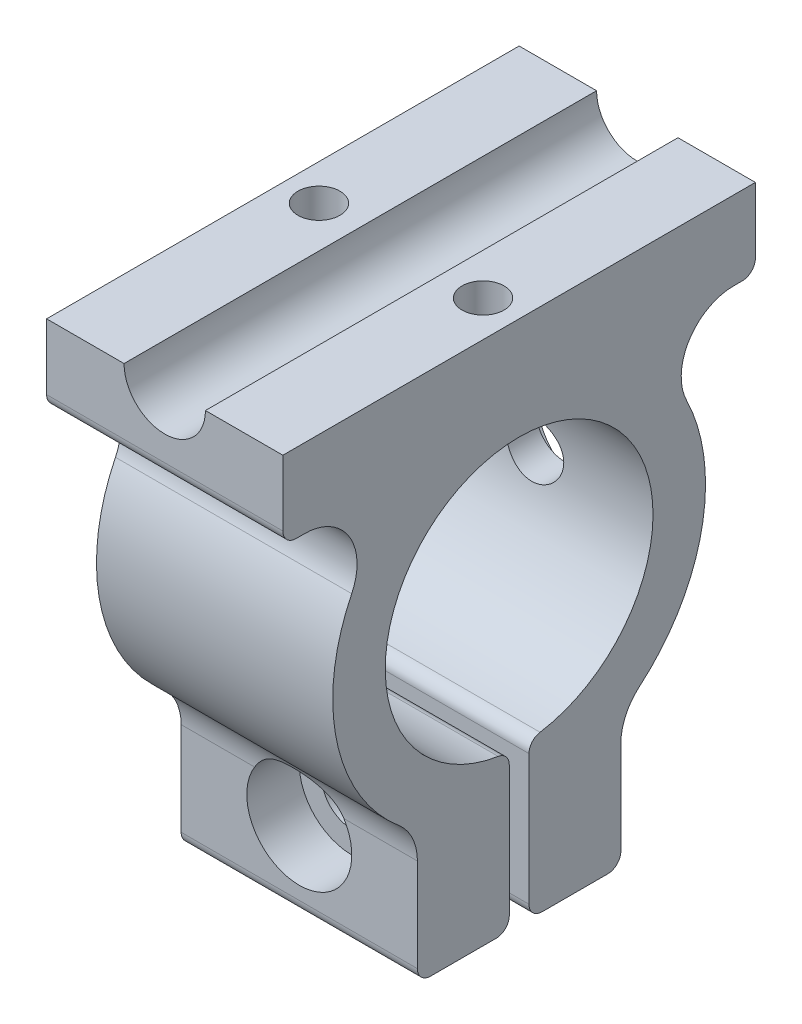
SolidWorks part; units mm, degrees
ref_plane "Спереди" through (0, 0, 0) normal (0, 0, 1) x (1, 0, 0)
ref_plane "Сверху" through (0, 0, 0) normal (0, 1, 0) x (1, 0, 0)
ref_plane "Справа" through (0, 0, 0) normal (1, 0, 0) x (0, 0, -1)
other "Configuration Table"
sketch "Эскиз1" plane through (0, 0, 0) normal (1, 0, 0) x (0, 0, -1)
  line L0 (-1001.0275, 18) -> (48998.9725, 18) construction
  line L1 (0, -1000) -> (0, 49000) construction
  line L2 (-0.75, -21) -> (-0.75, -11.0624)
  line L3 (0.75, -21) -> (0.75, -11.0624)
  line L4 (7.75, -13.8988) -> (7.75, -21)
  line L5 (-7.75, -13.8988) -> (-7.75, -21)
  line L6 (1.75, -22) -> (6.75, -22)
  line L7 (-1000, 0) -> (49000, 0) construction
  line L8 (-6.75, -22) -> (-1.75, -22)
  line L9 (-18, 18) -> (-18, 13)
  line L10 (-7.75, -6.6316) -> (-7.75, -11.8986) construction
  line L11 (7.75, -6.6316) -> (7.75, -11.8986) construction
  line L12 (-17, 12) -> (-16.3475, 12)
  line L13 (17, 12) -> (16.3475, 12)
  line L14 (18, 18) -> (18, 13)
  line L15 (-18, 18) -> (18, 18)
  arc A0 (1.5938, -10.0747) -> (-1.5938, -10.0747) centre (0, 0) ccw
  arc A1 (9.1676, -10.8441) -> (12.7546, 6.2418) centre (0, 0) ccw
  arc A2 (0, -10.2) -> (0.75, -10.1724) centre (0, 0) ccw construction
  arc A3 (-0.75, -10.1724) -> (0, -10.2) centre (0, 0) ccw construction
  arc A4 (0, -14.2) -> (0.75, -14.1802) centre (0, 0) ccw construction
  arc A5 (-0.75, -14.1802) -> (0, -14.2) centre (0, 0) ccw construction
  arc A6 (-7.75, -11.8986) -> (-0.75, -14.1802) centre (0, 0) ccw construction
  arc A7 (0.75, -14.1802) -> (7.75, -11.8986) centre (0, 0) ccw construction
  arc A8 (0, 14.2) -> (-7.5921, 12) centre (0, 0) ccw construction
  arc A9 (-12.7546, 6.2418) -> (-9.1676, -10.8441) centre (0, 0) ccw
  arc A10 (7.5921, 12) -> (0, 14.2) centre (0, 0) ccw construction
  arc A11 (16.3475, 12) -> (12.7546, 6.2418) centre (16.3475, 8) ccw
  arc A12 (-16.3475, 12) -> (-12.7546, 6.2418) centre (-16.3475, 8) cw
  arc A13 (9.1676, -10.8441) -> (7.75, -13.8988) centre (11.75, -13.8988) ccw
  arc A14 (-9.1676, -10.8441) -> (-7.75, -13.8988) centre (-11.75, -13.8988) cw
  arc A15 (18, 13) -> (17, 12) centre (17, 13) cw
  arc A16 (-18, 13) -> (-17, 12) centre (-17, 13) ccw
  arc A17 (1.5938, -10.0747) -> (0.75, -11.0624) centre (1.75, -11.0624) ccw
  arc A18 (-0.75, -11.0624) -> (-1.5938, -10.0747) centre (-1.75, -11.0624) ccw
  arc A19 (7.75, -21) -> (6.75, -22) centre (6.75, -21) cw
  arc A20 (-7.75, -21) -> (-6.75, -22) centre (-6.75, -21) ccw
  arc A21 (1.75, -22) -> (0.75, -21) centre (1.75, -21) cw
  arc A22 (-0.75, -21) -> (-1.75, -22) centre (-1.75, -21) cw
  point P43 (18, 12)
  point P46 (-18, 12)
  point P55 (7.75, -22)
  point P58 (-7.75, -22)
  point P63 (-0.75, -22)
  dimension "D1" = 20.4
  dimension "D2" = 4
  dimension "D9" = 4
  dimension "D10" = 4
  dimension "D11" = 4
  dimension "D12" = 4
  dimension "D13" = 1
  dimension "D14" = 1
  dimension "D15" = 1
  dimension "D16" = 1
  dimension "D17" = 1
  dimension "D18" = 1
  dimension "D19" = 1
  dimension "D20" = 1
  dimension "D3" = 18
  dimension "D4" = 1.5
  dimension "D5" = 15.5
  dimension "D6" = 36
  dimension "D7" = 6
  dimension "D8" = 22
extrude "Бобышка-Вытянуть1" add sketch "Эскиз1" along normal mid plane 18
sketch "Эскиз2" plane through (0, 0, 0) normal (0, 0, 1) x (1, 0, 0)
  line L0 (9, -22) -> (-9, -22) construction
  line L1 (9, -22) -> (-9, -22)
  line L2 (0, -1000) -> (0, 49000) construction
  line L3 (9, 18) -> (-9, 18) construction
  line L4 (9, 18) -> (-9, 18)
  circle A0 centre (0, -16) radius 2.3
  arc A1 (-3.1, 18) -> (3.1, 18) centre (0, 18) ccw
  arc A2 (3.1, 18) -> (0, 21.1) centre (0, 18) ccw construction
  arc A3 (0, 21.1) -> (-3.1, 18) centre (0, 18) ccw construction
  dimension "D2" = 4.6
  dimension "D3" = 6.2
  dimension "D1" = 6
extrude "Вырез-Вытянуть1" cut sketch "Эскиз2" against normal through all both and the other way through all contours L4 A1 | A0
sketch "Эскиз3" plane through (0, 0, -7.75) normal (0, 0, -1) x (-1, 0, 0)
  line L0 (0, -1016) -> (0, 48984) construction
  line L1 (-1000, -16) -> (49000, -16) construction
  line L3 (-4.6188, -16) -> (-2.3094, -20)
  line L4 (-2.3094, -20) -> (2.3094, -20)
  line L5 (9, -13.8988) -> (0.9355, -13.8988)
  line L6 (-0.9355, -13.8988) -> (-9, -13.8988)
  line L7 (-9, -13.8988) -> (-9, -21)
  line L8 (-9, -21) -> (9, -21)
  line L9 (9, -21) -> (9, -13.8988)
  line L10 (9, -13.8988) -> (0.9355, -13.8988)
  line L11 (-0.9355, -13.8988) -> (-9, -13.8988)
  line L12 (-9, -13.8988) -> (-9, -21)
  line L13 (-9, -21) -> (9, -21)
  line L14 (9, -21) -> (9, -13.8988)
  line L15 (2.3094, -20) -> (4.6188, -16)
  line L16 (4.6188, -16) -> (2.3094, -12)
  line L17 (2.3094, -12) -> (-2.3094, -12)
  line L18 (-2.3094, -12) -> (-4.6188, -16)
  circle A0 centre (0, -16) radius 4 construction
  arc A1 (-0.9355, -13.8988) -> (0.9355, -13.8988) centre (0, -16) ccw
  arc A2 (-0.9355, -13.8988) -> (0.9355, -13.8988) centre (0, -16) ccw
  arc M10 (0.9355, -13.8988) -> (-0.9355, -13.8988) centre (0, -16) cw
  line M11 (-0.9355, -13.8988) -> (-9, -13.8988)
  dimension "D2" = 8
  dimension "D1" = 0
extrude "Вырез-Вытянуть2" cut sketch "Эскиз3" against normal blind 3.3 and the other way through all draft 1 contours L18 L3 L4 L15 L16 L10 M11 M10 | L17 L18 L10 L16 M11 M10
sketch "Эскиз4" plane through (0, 0, 7.75) normal (0, 0, 1) x (1, 0, 0)
  arc A0 (-0.9355, -13.8988) -> (0.9355, -13.8988) centre (0, -16) ccw construction
  arc A1 (-0.9355, -13.8988) -> (0.9355, -13.8988) centre (0, -16) ccw
  circle A2 centre (0, -16) radius 4
  line M1 (9, -13.8988) -> (0.9355, -13.8988)
  arc M2 (0.9355, -13.8988) -> (-0.9355, -13.8988) centre (0, -16) cw
  line M3 (-0.9355, -13.8988) -> (-9, -13.8988)
  dimension "D1" = 8
extrude "Вырез-Вытянуть3" cut sketch "Эскиз4" against normal blind 4 and the other way through all contours A2 M3 M1 M2 | A2 M1 M3 M2
sketch "Эскиз5" plane through (0, 18, 0) normal (0, 1, 0) x (1, 0, 0)
  line L0 (-1000, 0) -> (49000, 0) construction
  line L1 (0, -1000) -> (0, 49000) construction
  circle A0 centre (6.25, 0) radius 1.6
  circle A1 centre (-6.25, 0) radius 1.6
  dimension "D1" = 3.2
  dimension "D2" = 12.5
extrude "Вырез-Вытянуть4" cut sketch "Эскиз5" against normal up to surface (7.9263 mm away)
sketch "Эскиз6" plane through (0, 0, 0) normal (0, 0, 1) x (1, 0, 0)
  circle A0 centre (0, 0) radius 2.2
  dimension "D1" = 4.4
extrude "Вырез-Вытянуть5" cut sketch "Эскиз6" against normal through all
sketch "Эскиз7" plane through (0, 0, -18) normal (0, 0, -1) x (-1, 0, 0)
  circle A0 centre (0, 0) radius 2.2 construction
  circle A1 centre (0, 0) radius 2.2
  circle A2 centre (0, 0) radius 4
  dimension "D1" = 8
extrude "Вырез-Вытянуть6" cut sketch "Эскиз7" against normal blind 5.5
